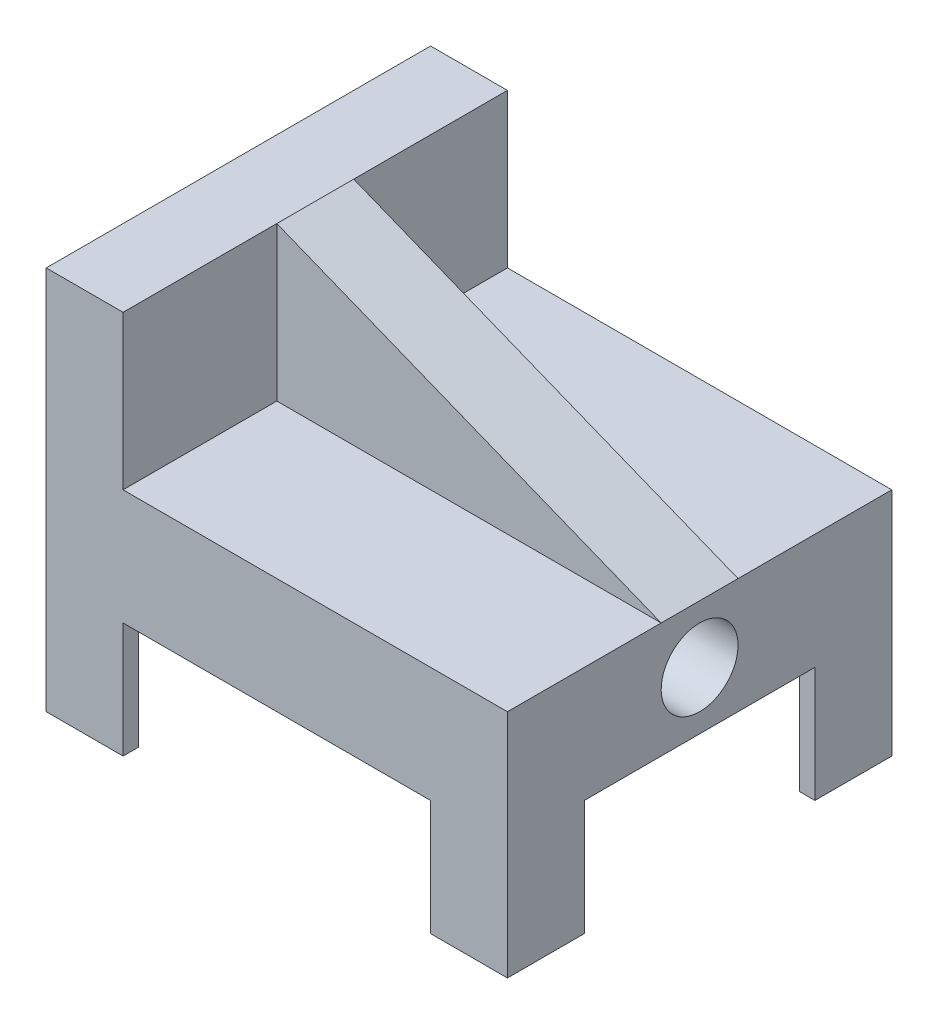
SolidWorks part; units mm, degrees
ref_plane "Front Plane" through (0, 0, 0) normal (0, 0, 1) x (1, 0, 0)
ref_plane "Top Plane" through (0, 0, 0) normal (0, 1, 0) x (1, 0, 0)
ref_plane "Right Plane" through (0, 0, 0) normal (1, 0, 0) x (0, 0, -1)
sketch "Sketch7" plane through (0, 0, 0) normal (0, 0, 1) x (1, 0, 0)
  line L1 (-59.9092, 9.4402) -> (60.0908, 9.4402)
  line L2 (-59.9092, 9.4402) -> (-59.9092, -20.5598)
  line L3 (-59.9092, -20.5598) -> (60.0908, -20.5598)
  line L4 (60.0908, 9.4402) -> (60.0908, -20.5598)
  dimension "D1" = 120
  dimension "D2" = 30
extrude "Boss-Extrude4" add sketch "Sketch7" against normal blind 100
sketch "Sketch8" plane through (0, 9.4402, 0) normal (0, 1, 0) x (1, 0, 0)
  line L0 (60.0908, 0) -> (-59.9092, 0) construction
  line L1 (-59.9092, 100) -> (-39.9092, 100)
  line L2 (-59.9092, 100) -> (-59.9092, 0)
  line L3 (-59.9092, 0) -> (-39.9092, 0)
  line L4 (-39.9092, 100) -> (-39.9092, 0)
  dimension "D1" = 20
extrude "Boss-Extrude5" add sketch "Sketch8" along normal blind 40 contours L2 L1 L4 L3
sketch "Sketch9" plane through (0, 9.4402, 0) normal (0, 1, 0) x (1, 0, 0)
  line L1 (-39.9092, 60) -> (60.0908, 60)
  line L2 (-39.9092, 60) -> (-39.9092, 40)
  line L3 (-39.9092, 40) -> (60.0908, 40)
  line L4 (60.0908, 60) -> (60.0908, 40)
  line L5 (60.0908, 100) -> (60.0908, 0) construction
  dimension "D1" = 20
extrude "Boss-Extrude6" add sketch "Sketch9" along normal blind 40 contours L2 L1 L4 L3
sketch "Sketch10" plane through (0, 0, -40) normal (0, 0, 1) x (1, 0, 0)
  line L0 (-39.9092, 49.4402) -> (60.0908, 9.4402)
extrude "Cut-Extrude2" cut sketch "Sketch10" against normal blind 40 and the other way through all
sketch "Sketch11" plane through (60.0908, 0, 0) normal (1, 0, 0) x (0, 0, -1)
  circle A0 centre (50, -5.5598) radius 10
  dimension "D1" = 20
extrude "Cut-Extrude3" cut sketch "Sketch11" against normal blind 120 contours A0
sketch "Sketch12" plane through (0, -20.5598, 0) normal (0, -1, 0) x (1, 0, 0)
  line L0 (0.0908, 0) -> (0.0908, -100)
  line L1 (60.0908, -100) -> (40.0908, -100)
  line L2 (60.0908, -100) -> (60.0908, -96)
  line L3 (60.0908, -96) -> (40.0908, -96)
  line L4 (40.0908, -100) -> (40.0908, -96)
  line L5 (60.0908, -100) -> (56.0908, -100)
  line L6 (60.0908, -100) -> (60.0908, -80)
  line L7 (60.0908, -80) -> (56.0908, -80)
  line L8 (56.0908, -100) -> (56.0908, -80)
  line L9 (-59.9092, 0) -> (60.0908, 0) construction
  line L10 (-59.9092, -100) -> (60.0908, -100) construction
  line L11 (-59.9092, -50) -> (60.0908, -50)
  line L12 (-59.9092, -100) -> (-59.9092, 0) construction
  line L13 (60.0908, -100) -> (60.0908, 0) construction
  line L14 (-59.9092, -96) -> (-39.9092, -96)
  line L15 (-39.9092, -100) -> (-39.9092, -96)
  line L16 (-59.9092, -100) -> (-39.9092, -100)
  line L17 (-59.9092, -100) -> (-59.9092, -96)
  line L18 (-59.9092, -80) -> (-55.9092, -80)
  line L19 (-55.9092, -100) -> (-55.9092, -80)
  line L20 (-59.9092, -100) -> (-55.9092, -100)
  line L21 (-59.9092, -100) -> (-59.9092, -80)
  line L22 (60.0908, -4) -> (40.0908, -4)
  line L23 (40.0908, 0) -> (40.0908, -4)
  line L24 (60.0908, 0) -> (40.0908, 0)
  line L25 (60.0908, 0) -> (60.0908, -4)
  line L26 (60.0908, -20) -> (56.0908, -20)
  line L27 (56.0908, 0) -> (56.0908, -20)
  line L28 (60.0908, 0) -> (56.0908, 0)
  line L29 (60.0908, 0) -> (60.0908, -20)
  line L30 (-59.9092, 0) -> (-55.9092, 0)
  line L31 (-55.9092, 0) -> (-55.9092, -20)
  line L32 (-59.9092, -20) -> (-55.9092, -20)
  line L33 (-59.9092, 0) -> (-59.9092, -20)
  line L34 (-59.9092, 0) -> (-39.9092, 0)
  line L35 (-39.9092, 0) -> (-39.9092, -4)
  line L36 (-59.9092, -4) -> (-39.9092, -4)
  line L37 (-59.9092, 0) -> (-59.9092, -4)
  line M1 (60.0908, 0) -> (-59.9092, 0)
  line M2 (-59.9092, 0) -> (-59.9092, -100)
  line M3 (-59.9092, -100) -> (60.0908, -100)
  line M4 (60.0908, -100) -> (60.0908, 0)
  dimension "D1" = 20
  dimension "D2" = 4
  dimension "D3" = 20
  dimension "D4" = 4
extrude "Boss-Extrude7" add sketch "Sketch12" along normal blind 30 contours L36 L33 L32 L31 | L36 L31 M2 M1 | L31 L36 L35 M1 | L27 L24 L23 L22 | L22 L27 L26 M4 | L27 L22 M1 M4 | L8 L3 L7 M4 | L8 L1 L3 M4 | L8 L3 L4 M3 | L16 L15 L14 L17 | L20 L19 L18 L21
